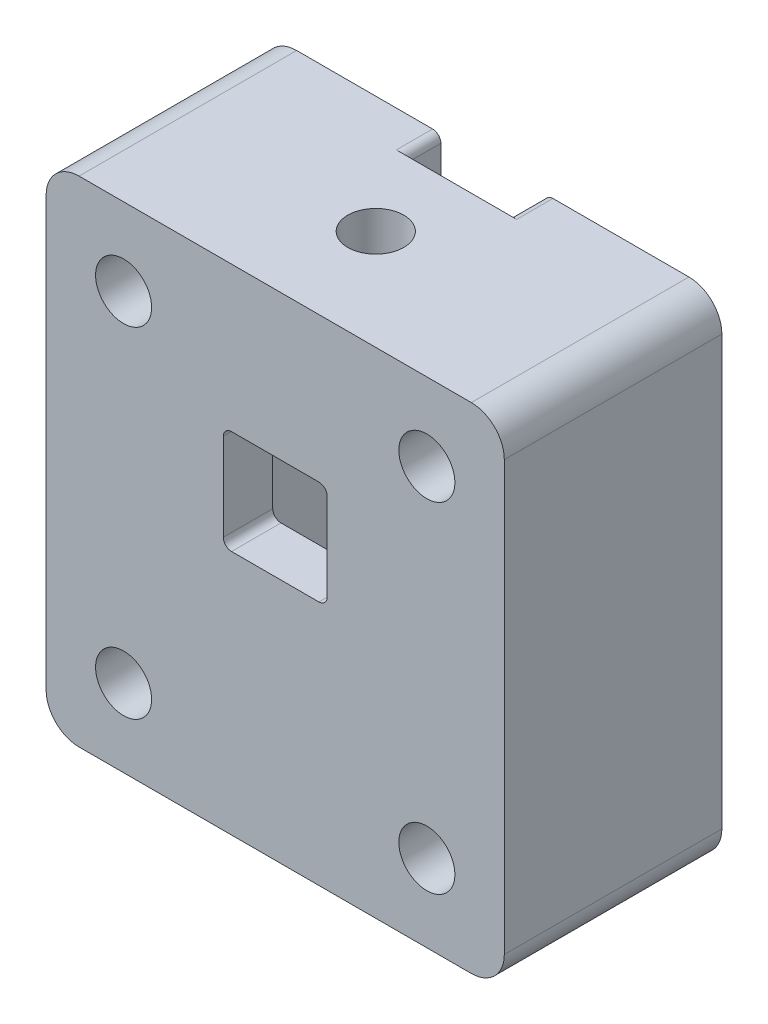
SolidWorks part; units mm, degrees
ref_plane "Front" through (0, 0, 0) normal (0, 0, 1) x (1, 0, 0)
ref_plane "Top" through (0, 0, 0) normal (0, 1, 0) x (1, 0, 0)
ref_plane "Right" through (0, 0, 0) normal (1, 0, 0) x (0, 0, -1)
sketch "Sketch2" plane through (0, 0, 0) normal (0, 1, 0) x (1, 0, 0)
  line L0 (0, -50) -> (0, 50) construction
  line L1 (-13.9, -6.6) -> (13.9, -6.6)
  line L2 (-13.9, -6.6) -> (-13.9, 6.6)
  line L3 (-13.9, 6.6) -> (13.9, 6.6)
  line L4 (13.9, -6.6) -> (13.9, 6.6)
  line L5 (-13.9, -6.6) -> (13.9, 6.6) construction
  line L6 (-13.9, 6.6) -> (13.9, -6.6) construction
  point P0 (0, 0)
  dimension "D2" = 13.9
  dimension "D1" = 13.2
extrude "Boss-Extrude1" add sketch "Sketch2" along normal mid plane 30
sketch "Sketch7" plane through (0, 0, 6.6) normal (0, 0, 1) x (1, 0, 0)
  line L1 (-13.9, 15) -> (-13.9, -15) construction
  line L2 (-13.9, 15) -> (13.9, 15) construction
  circle A0 centre (-9.2, 10.3) radius 1.7
  point P8 (-9.2, 10.3)
  dimension "D3" = 3.4
  dimension "D1" = 4.7
  dimension "D2" = 4.7
extrude "Cut-Extrude1" cut sketch "Sketch7" against normal through all
mirror "Mirror1" about plane through (0, 0, 0) normal (1, 0, 0) of "Cut-Extrude1"
mirror "Mirror2" about plane through (0, 0, 0) normal (0, 1, 0) of "Mirror1", "Cut-Extrude1"
sketch "Sketch8" plane through (0, -15, 0) normal (0, -1, 0) x (1, 0, 0)
  line L0 (0, -50) -> (0, 50) construction
  line L1 (-4.15, -6.6) -> (4.15, -6.6)
  line L2 (-4.15, -6.6) -> (-4.15, 3.6)
  line L3 (-4.15, 3.6) -> (4.15, 3.6)
  line L4 (4.15, -6.6) -> (4.15, 3.6)
  line L5 (-4.15, -6.6) -> (4.15, 3.6) construction
  line L6 (-4.15, 3.6) -> (4.15, -6.6) construction
  line L7 (13.9, -6.6) -> (-13.9, -6.6) construction
  point P0 (0, -1.5)
  dimension "D1" = 10.2
  dimension "D2" = 8.3
extrude "Cut-Extrude2" cut sketch "Sketch8" against normal blind 21.2
sketch "Sketch11" plane through (4.15, 0, 0) normal (-1, 0, 0) x (0, 0, 1)
  line L0 (-11.6, 15) -> (-4.4, 15)
  line L1 (-4.4, 15) -> (-4.4, 14.2)
  line L2 (-4.4, 14.2) -> (-3.8, 14.2)
  line L3 (-3.8, 14.2) -> (-3.8, 13)
  line L4 (-3.8, 13) -> (-4.4, 13)
  line L5 (-4.4, 13) -> (-4.4, 12.2)
  line L6 (-4.4, 12.2) -> (-3.8, 12.2)
  line L7 (-3.8, 12.2) -> (-3.8, 11)
  line L8 (-3.8, 11) -> (-4.4, 11)
  line L9 (-4.4, 11) -> (-4.4, 10.2)
  line L10 (-4.4, 10.2) -> (-3.8, 10.2)
  line L11 (-3.8, 10.2) -> (-3.8, 9)
  line L12 (-3.8, 9) -> (-4.4, 9)
  line L13 (-4.4, 9) -> (-4.4, 8.2)
  line L14 (-4.4, 8.2) -> (-3.8, 8.2)
  line L15 (-3.8, 8.2) -> (-3.8, 7)
  line L16 (-3.8, 7) -> (-4.4, 7)
  line L17 (-4.4, 7) -> (-4.4, 6.2)
  line L18 (-4.4, 6.2) -> (-11.6, 6.2)
  line L19 (-11.6, 6.2) -> (-11.6, 15)
  line L21 (-6.6, 6.2) -> (-6.6, -15) construction
  line L22 (-6.6, 6.2) -> (3.6, 6.2) construction
  line L23 (-11.6, 10.6) -> (-4.4, 10.6) construction
  point P24 (-6.6, 15)
  dimension "D1" = 1.2
  dimension "D2" = 0.8
  dimension "D3" = 0.6
  dimension "D4" = 2.2
  dimension "D5" = 5
extrude "Cut-Extrude5" cut sketch "Sketch11" along normal offset from surface (6.3 mm away) 1 from offset 1 up to face at (-4.15, -4.4, -1.5)
sketch "Sketch12" plane through (0, 0, 3.6) normal (0, 0, -1) x (-1, 0, 0)
  line L0 (0, 50) -> (0, -50) construction
  line L2 (-3.15, -0.1) -> (3.15, -0.1)
  line L3 (-3.15, -0.1) -> (-3.15, 6.2)
  line L4 (-3.15, 6.2) -> (3.15, 6.2)
  line L5 (3.15, -0.1) -> (3.15, 6.2)
  line L6 (-3.15, -0.1) -> (3.15, 6.2) construction
  line L7 (-3.15, 6.2) -> (3.15, -0.1) construction
  line L8 (4.15, 6.2) -> (4.15, -15) construction
  line L9 (-4.15, 6.2) -> (4.15, 6.2) construction
  point P2 (0, 3.05)
  dimension "D2" = 1
  dimension "D3" = 6.3
  dimension "D4" = 6.3
extrude "Cut-Extrude6" cut sketch "Sketch12" against normal through all
fillet "Fillet4" radius 0.5 4 edges at (-3.15, -0.1, 5.1) (-3.15, 6.2, 5.1) (3.15, -0.1, 5.1) (3.15, 6.2, 5.1)
fillet "Fillet3" radius 2 4 edges at (13.9, -15, 0) (13.9, 15, 0) (-13.9, -15, 0) (-13.9, 15, 0)
fillet "Fillet5" radius 0.5 6 edges at (-4.15, -15, -1.5) (4.15, -15, -1.5) (-3.15, 15, -5.5) (3.15, 15, -5.5) (-3.15, 6.2, -5.5) (3.15, 6.2, -5.5)
sketch "Sketch13" plane through (0, 6.2, 0) normal (0, -1, 0) x (1, 0, 0)
  line L0 (0, -50) -> (0, 50) construction
  line L2 (4.65, 3.6) -> (-4.65, 3.6) construction
  circle A0 centre (0, 0.5) radius 1.7
  dimension "D2" = 3.4
  dimension "D1" = 3.1
extrude "Cut-Extrude7" cut sketch "Sketch13" against normal through all
equation "\"M3_d\"= 3.4"
equation "\"linear_bearing_d\"= 12"
equation "\"linear_bearing_l\"= 30"
equation "\"D1@Boss-Extrude1\"= \"linear_bearing_l\""
equation "\"t\"= 3"
equation "\"D2@Sketch2\"= \"linear_bearing_d\" / 2 + \"t\" / 2 + \"M3_d\" + \"t\""
equation "\"D3@Sketch7\"= \"M3_d\""
equation "\"D1@Sketch7\"= \"M3_d\" / 2 + \"t\" "
equation "\"D2@Sketch7\"=\"D1@Sketch7\""
equation "\"groove_big_b\"= 8.2 + 0.1"
equation "\"D2@Sketch8\"=\"groove_big_b\""
equation "\"groove_small_l\"= 9 - 0.2"
equation "\"D1@Cut-Extrude2\"= \"linear_bearing_l\" - \"groove_small_l\""
equation "\"groove_small_b\"= 6.2 + 0.1"
equation "\"groove_h\"= 1.7 + 0.5"
equation "\"D4@Sketch11\"= \"groove_h\""
equation "\"tensioner_h\" = 7.8 + 0.2"
equation "\"D1@Sketch2\"= \"tensioner_h\" + \"groove_h\" + \"t\""
equation "\"D1@Sketch8\"=\"tensioner_h\" + \"groove_h\""
equation "\"D4@Sketch12\"= \"D3@Sketch12\""
equation "\"M3_nut_m_XY\"= 6.2"
equation "\"D2@Sketch13\"=\"M3_d\""
equation "\"D19@Cut-Extrude5\"=(\"groove_big_b\" - \"groove_small_b\") / 2"
equation "\"D1@Cut-Extrude5\"=(\"groove_big_b\" - \"groove_small_b\") / 2"
equation "\"D1@Sketch13\"=\"M3_nut_m_XY\" / 2"
